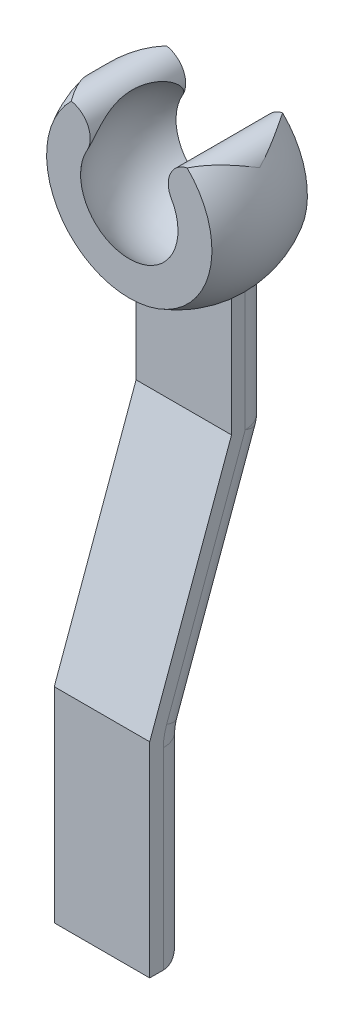
SolidWorks part; units mm, degrees
ref_plane "Front" through (0, 0, 0) normal (0, 0, 1) x (1, 0, 0)
ref_plane "Top" through (0, 0, 0) normal (0, 1, 0) x (1, 0, 0)
ref_plane "Right" through (0, 0, 0) normal (1, 0, 0) x (0, 0, -1)
sketch "Sketch1" plane through (0, 0, 0) normal (1, 0, 0) x (0, 0, -1)
  line L0 (0, 0) -> (0, 15)
  line L1 (0, 15) -> (6, 31.4849)
  line L2 (0, 0) -> (3, 0)
  line L3 (3, 0) -> (3, 14.471)
  line L4 (3, 14.471) -> (9, 30.9559)
  line L5 (3, 14.471) -> (0, 15) construction
  line L6 (1.5, 14.7355) -> (0, 14.7355) construction
  line L7 (1.5, 14.7355) -> (0.0905, 15.2485) construction
  line L8 (6, 31.4849) -> (6, 46.4849)
  line L9 (6, 46.4849) -> (9, 46.4849)
  line L10 (9, 46.4849) -> (9, 30.9559)
  line L11 (6, 31.4849) -> (9, 30.9559) construction
  line L12 (8.9095, 30.7073) -> (7.5, 31.2204) construction
  line L13 (7.5, 31.2204) -> (9, 31.2204) construction
  dimension "D1" = 3
  dimension "D2" = 15
  dimension "D3" = 160
  dimension "D4" = 15
  dimension "D5" = 6
extrude "Boss-Extrude1" add sketch "Sketch1" along normal mid plane 7
sketch "Sketch2" plane through (0, 46.4849, 0) normal (0, 1, 0) x (1, 0, 0)
  line L0 (0, 2) -> (0, 9)
  line L2 (0, 9) -> (6.0622, 9)
  line L3 (0, 2) -> (6.0622, 2)
  line L4 (3.5, 9) -> (-3.5, 9) construction
  arc A0 (6.0622, 2) -> (6.0622, 9) centre (0, 5.5) ccw
  point P0 (0, 5.5)
  dimension "D1" = 7
  dimension "D2" = 7
revolve "Revolve1" add sketch "Sketch2" angle 360 about L0
sketch "Sketch3" plane through (0, 0, 0) normal (1, 0, 0) x (0, 0, -1)
  line L0 (2, 46.4849) -> (9, 46.4849)
  line L1 (2, 52.547) -> (2, 40.4227) construction
  line L2 (9, 41.5351) -> (9, 52.547) construction
  line L3 (9, 46.4849) -> (9, 42.9142)
  line L4 (2, 46.4849) -> (2, 42.9142)
  arc A0 (2, 42.9142) -> (9, 42.9142) centre (5.5, 46.4849) ccw
  point P10 (5.5, 46.4849)
  dimension "D1" = 5
revolve "Cut-Revolve1" cut sketch "Sketch3" angle 360 about L0
sketch "Sketch4" plane through (0, 0, -2) normal (0, 0, 1) x (1, 0, 0)
  line L0 (-3.0923, 48.2702) -> (-6.0622, 49.9849) construction
  line L1 (3.0923, 48.2702) -> (6.0622, 49.9849) construction
  line L2 (-3.0923, 48.2702) -> (0, 46.4849) construction
  line L3 (0, 46.4849) -> (3.0923, 48.2702) construction
  line L4 (0, 46.4849) -> (0, 48.9645) construction
  circle A0 centre (0, 46.4849) radius 3.5707 construction
  circle A1 centre (0, 46.4849) radius 7 construction
  arc A2 (-3.0923, 48.2702) -> (-6.0622, 49.9849) centre (-4.5773, 49.1275) ccw
  arc A3 (3.0923, 48.2702) -> (6.0622, 49.9849) centre (4.5773, 49.1275) cw
  arc A4 (-3.0923, 48.2702) -> (3.0923, 48.2702) centre (0, 46.4849) cw
  arc A5 (6.0622, 49.9849) -> (-6.0622, 49.9849) centre (0, 46.4849) ccw
  point P13 (-4.5773, 49.1275)
  dimension "D1" = 120
extrude "Cut-Extrude1" cut sketch "Sketch4" against normal through all
fillet "Fillet10" radius 2 9 edges at (0, 14.471, -3) (0, 30.9559, -9) (-3.5, 36.2455, -9) (-3.5, 22.7135, -6) (-3.5, 7.2355, -3) (0, 0, -3) (3.5, 36.2455, -9) (3.5, 22.7135, -6) (3.5, 7.2355, -3)
